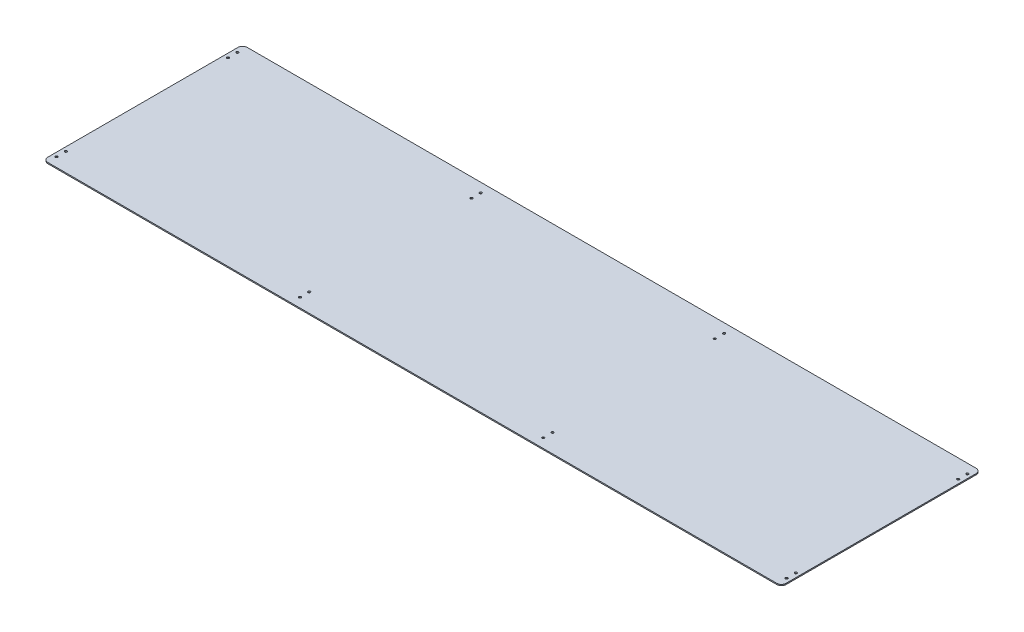
SolidWorks part; units mm, degrees
material "PC High Viscosity"
ref_plane "Front Plane" through (0, 0, 0) normal (0, 0, 1) x (1, 0, 0)
ref_plane "Top Plane" through (0, 0, 0) normal (0, 1, 0) x (1, 0, 0)
ref_plane "Right Plane" through (0, 0, 0) normal (1, 0, 0) x (0, 0, -1)
sketch "Sketch1" plane through (0, 0, 0) normal (0, 1, 0) x (1, 0, 0)
  line L1 (12.7, 0) -> (2009.775, 0)
  line L2 (0, 12.7) -> (0, 533.4)
  line L3 (12.7, 546.1) -> (2009.775, 546.1)
  line L4 (2022.475, 12.7) -> (2022.475, 533.4)
  circle A0 centre (11.1125, 520.7) radius 3.175
  circle A1 centre (11.1125, 495.3) radius 3.175
  circle A2 centre (11.1125, 50.8) radius 3.175
  circle A3 centre (11.1125, 25.4) radius 3.175
  circle A4 centre (677.8625, 520.7) radius 3.175
  circle A5 centre (677.8625, 495.3) radius 3.175
  circle A6 centre (677.8625, 50.8) radius 3.175
  circle A7 centre (677.8625, 25.4) radius 3.175
  circle A8 centre (1344.6125, 520.7) radius 3.175
  circle A9 centre (1344.6125, 495.3) radius 3.175
  circle A10 centre (1344.6125, 50.8) radius 3.175
  circle A11 centre (1344.6125, 25.4) radius 3.175
  circle A12 centre (2011.3625, 520.7) radius 3.175
  circle A13 centre (2011.3625, 495.3) radius 3.175
  circle A14 centre (2011.3625, 50.8) radius 3.175
  circle A15 centre (2011.3625, 25.4) radius 3.175
  arc A16 (2009.775, 0) -> (2022.475, 12.7) centre (2009.775, 12.7) ccw
  arc A17 (2009.775, 546.1) -> (2022.475, 533.4) centre (2009.775, 533.4) cw
  arc A18 (0, 533.4) -> (12.7, 546.1) centre (12.7, 533.4) cw
  arc A19 (12.7, 0) -> (0, 12.7) centre (12.7, 12.7) cw
  point P41 (2022.475, 546.1)
  point P44 (0, 546.1)
  point P47 (0, 0)
  dimension "D4" = 6.35
  dimension "D6" = 6.35
  dimension "D10" = 6.35
  dimension "D11" = 6.35
  dimension "D14" = 11.1125
  dimension "D17" = 12.7
  dimension "D1" = 2022.475
  dimension "D2" = 546.1
  dimension "D3" = 11.1125
  dimension "D5" = 25.4
  dimension "D7" = 25.4
  dimension "D8" = 11.1125
  dimension "D9" = 444.5
  dimension "D12" = 25.4
  dimension "D13" = 11.1125
  dimension "D16" = 666.75
  dimension "D15" = 4
extrude "Boss-Extrude1" add sketch "Sketch1" along normal blind 3.175
